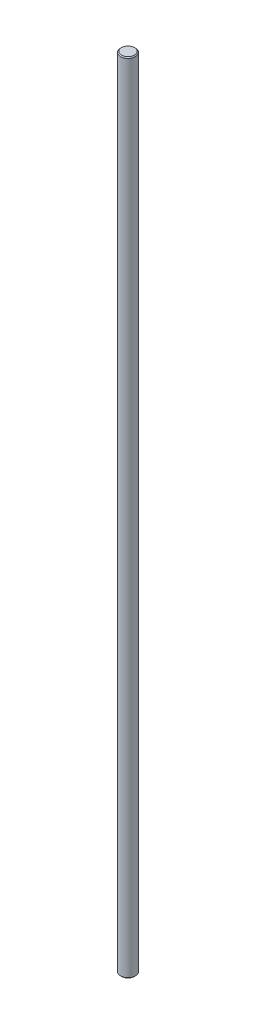
SolidWorks part; units mm, degrees
ref_plane "Front Plane" through (0, 0, 0) normal (0, 0, 1) x (1, 0, 0)
ref_plane "Top Plane" through (0, 0, 0) normal (0, 1, 0) x (1, 0, 0)
ref_plane "Right Plane" through (0, 0, 0) normal (1, 0, 0) x (0, 0, -1)
sketch "Sketch1" plane through (0, 0, 0) normal (0, 1, 0) x (1, 0, 0)
  circle A0 centre (0, 0) radius 4
  dimension "D1" = 8
extrude "Boss-Extrude1" add sketch "Sketch1" along normal mid plane 430
chamfer "Chamfer1" distance 0.5 angle 45 2 edges at (0, -215, 4) (0, 215, 4)
